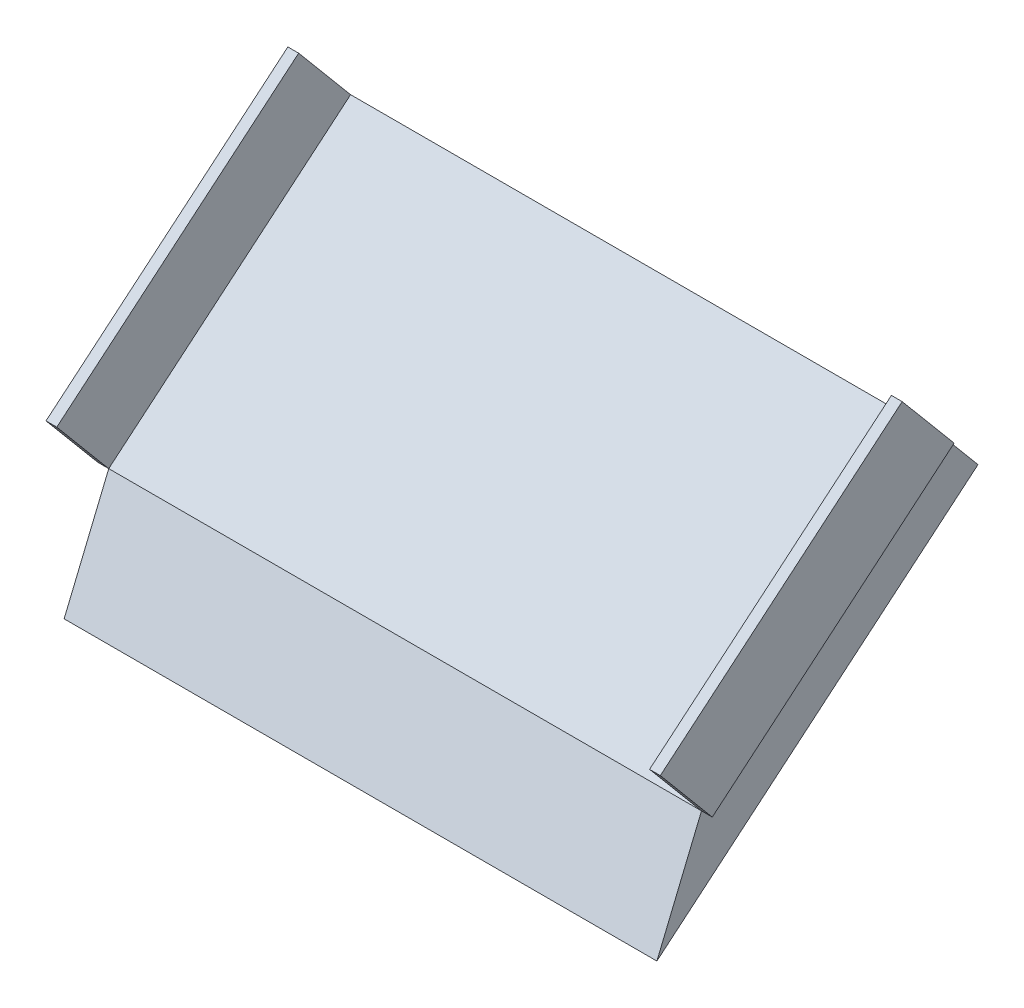
SolidWorks part; units mm, degrees
ref_plane "Front Plane" through (0, 0, 0) normal (0, 0, 1) x (1, 0, 0)
ref_plane "Top Plane" through (0, 0, 0) normal (0, 1, 0) x (1, 0, 0)
ref_plane "Right Plane" through (0, 0, 0) normal (1, 0, 0) x (0, 0, -1)
sketch "Sketch1" plane through (0, 0, 0) normal (1, 0, 0) x (0, 0, -1)
  line L0 (0, 0) -> (-357.5261, -300)
  line L1 (0, 0) -> (0, -300) construction
  line L2 (0, -300) -> (-1296.5357, -300) construction
  line L3 (0, 0) -> (-64.2788, 76.6044)
  line L4 (-64.2788, 76.6044) -> (-513.0985, -300)
  line L5 (-357.5261, -300) -> (-357.5261, -500) construction
  line L6 (-362.1669, -500) -> (-638.2522, -500) construction
  line L8 (-357.5261, -300) -> (0, 0)
  line L9 (-357.5261, -300) -> (-595.8768, -500)
  line L10 (-513.0985, -300) -> (-595.8768, -500)
  dimension "D1" = 200
  dimension "D2" = 300
  dimension "D3" = 100
extrude "Boss-Extrude2" add sketch "Sketch1" along normal blind 1100
sketch "Sketch2" plane through (1100, 0, 0) normal (1, 0, 0) x (0, 0, -1)
  line L0 (-609.5166, -185.0933) -> (-513.0985, -300)
  line L4 (-160.6969, 191.5111) -> (-609.5166, -185.0933)
  line L6 (-513.0985, -300) -> (-64.2788, 76.6044)
  line L7 (-64.2788, 76.6044) -> (-160.6969, 191.5111)
  dimension "D1" = 150
extrude "Boss-Extrude3" add sketch "Sketch2" along normal blind 20 separate body
sketch "Sketch3" plane through (0, 0, 0) normal (-1, 0, 0) x (0, 0, 1)
  line L0 (64.2788, 76.6044) -> (160.6969, 191.5111)
  line L1 (160.6969, 191.5111) -> (609.5166, -185.0933)
  line L2 (609.5166, -185.0933) -> (513.0985, -300)
  line L3 (513.0985, -300) -> (64.2788, 76.6044)
extrude "Boss-Extrude4" add sketch "Sketch3" along normal blind 20 separate body
